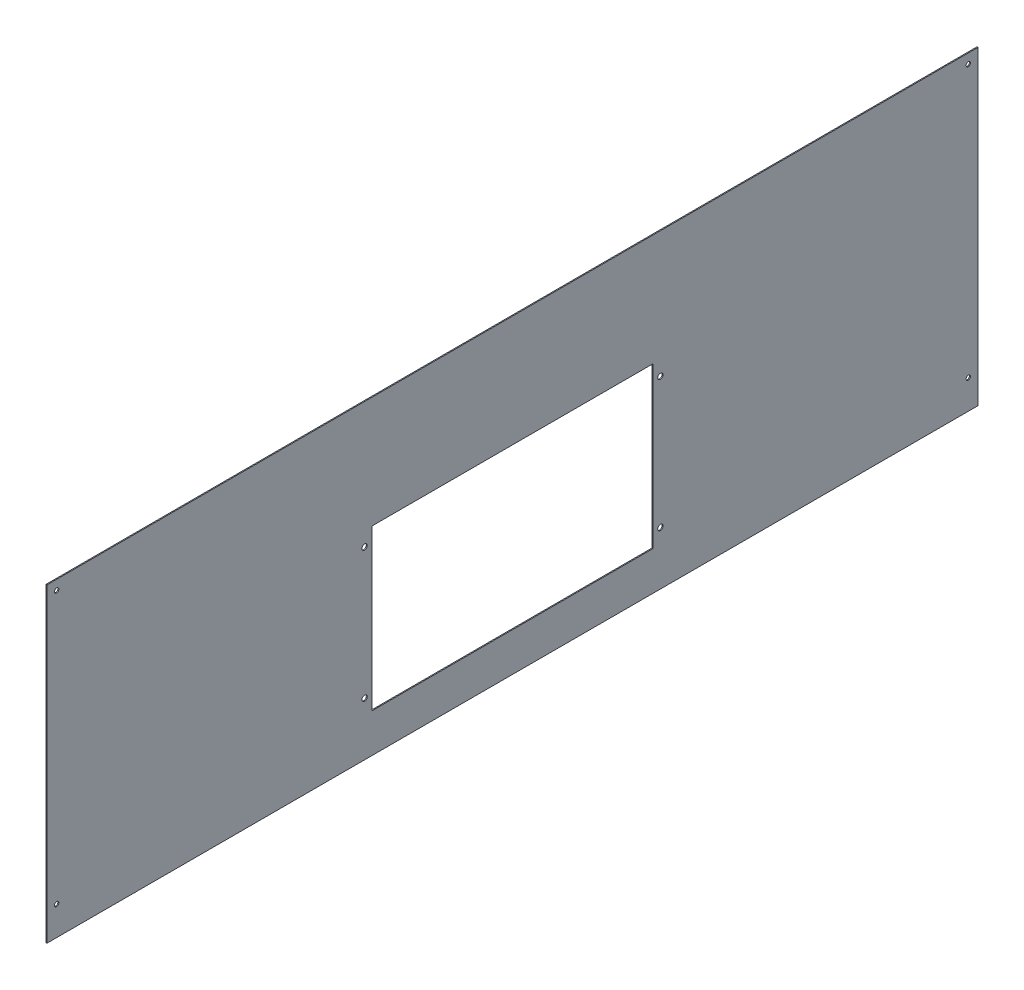
SolidWorks part; units mm, degrees
ref_plane "Front Plane" through (0, 0, 0) normal (0, 0, 1) x (1, 0, 0)
ref_plane "Top Plane" through (0, 0, 0) normal (0, 1, 0) x (1, 0, 0)
ref_plane "Right Plane" through (0, 0, 0) normal (1, 0, 0) x (0, 0, -1)
sketch "Sketch1" plane through (0, 0, 0) normal (1, 0, 0) x (0, 0, -1)
  line L1 (-960, -320) -> (960, -320)
  line L2 (-960, -320) -> (-960, 320)
  line L3 (-960, 320) -> (960, 320)
  line L4 (960, -320) -> (960, 320)
  line L5 (-960, -320) -> (960, 320) construction
  line L6 (-960, 320) -> (960, -320) construction
  line L7 (-290, -240) -> (290, -240)
  line L8 (-290, -240) -> (-290, 90)
  line L9 (-290, 90) -> (290, 90)
  line L10 (290, -240) -> (290, 90)
  circle A0 centre (-940, 300) radius 4.5
  circle A1 centre (940, 300) radius 4.5
  circle A2 centre (940, -260) radius 4.5
  circle A3 centre (-940, -260) radius 4.5
  circle A4 centre (-305, 60) radius 5.5
  circle A5 centre (305, 60) radius 5.5
  circle A6 centre (305, -210) radius 5.5
  circle A7 centre (-305, -210) radius 5.5
  point P0 (0, 0)
  point P19 (0, 90)
  dimension "D3" = 9
  dimension "D8" = 580
  dimension "D11" = 11
  dimension "D14" = 2
  dimension "D1" = 1920
  dimension "D2" = 640
  dimension "D4" = 20
  dimension "D5" = 20
  dimension "D6" = 60
  dimension "D7" = 20
  dimension "D9" = 330
  dimension "D10" = 80
  dimension "D12" = 15
  dimension "D13" = 30
  dimension "D16" = 270
  dimension "D17" = 305
  dimension "D18" = 210
  dimension "D15" = 2
surface "Surface-Plane1" sketch "Sketch1"
thicken "Thicken1" surfaces to thicken 101 thickness 2 parameters "D1"=2
